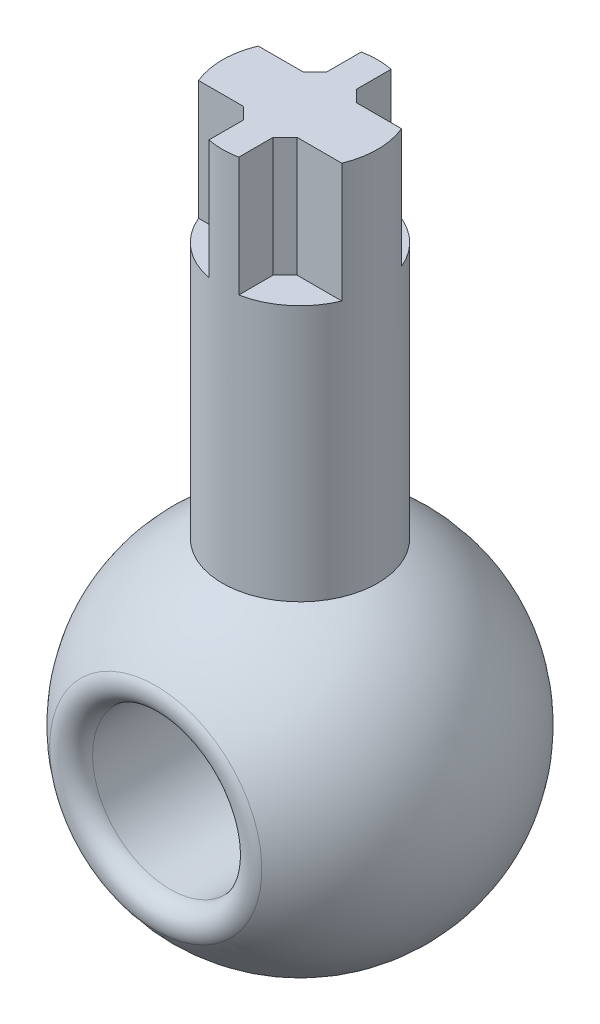
SolidWorks part; units mm, degrees
ref_plane "Plane1" through (0, 0, 0) normal (0, 0, 1) x (1, 0, 0)
ref_plane "Plane2" through (0, 0, 0) normal (0, 1, 0) x (1, 0, 0)
ref_plane "Plane3" through (0, 0, 0) normal (1, 0, 0) x (0, 0, -1)
sketch "s1" plane through (0, 0, 0) normal (0, 0, 1) x (1, 0, 0)
  line L0 (-56.6721, 0) -> (83.8972, 0) construction
  line L1 (-15, 0) -> (15, 0)
  arc A0 (15, 0) -> (-15, 0) centre (0, 0) ccw
  dimension "D1" = 15
revolve "1" add sketch "s1" angle 360 about L0
sketch "s2" plane through (0, 0, 0) normal (0, 1, 0) x (1, 0, 0)
  circle A0 centre (0, 0) radius 6.5
  dimension "D1" = 13
extrude "2" add sketch "s2" along normal blind 45
sketch "s3" plane through (0, 45, 0) normal (0, 1, 0) x (-1, 0, 0)
  line L0 (-10.6288, 0) -> (13.9677, 0) construction
  line L1 (56.6721, 0) -> (-83.8972, 0) construction
  line L2 (0, -10.8514) -> (0, 14.1903) construction
  line L3 (-1.25, -6.3787) -> (-1.25, -2.5)
  line L4 (1.25, -6.3787) -> (1.25, -2.5)
  line L5 (-6, 2.5) -> (-1.25, 2.5)
  line L6 (-6, -2.5) -> (-1.25, -2.5)
  line L7 (-1.25, 2.5) -> (-1.25, 6.3787)
  line L8 (1.25, 2.5) -> (1.25, 6.3787)
  line L9 (1.25, -2.5) -> (6, -2.5)
  line L10 (1.25, 2.5) -> (6, 2.5)
  circle A0 centre (0, 0) radius 6.5 construction
  arc A1 (-6, -2.5) -> (-1.25, -6.3787) centre (0, 0) ccw
  arc A2 (6, 2.5) -> (1.25, 6.3787) centre (0, 0) ccw
  arc A3 (-1.25, 6.3787) -> (-6, 2.5) centre (0, 0) ccw
  arc A4 (1.25, -6.3787) -> (6, -2.5) centre (0, 0) ccw
  dimension "D1" = 5
  dimension "D2" = 2.5
extrude "3" cut sketch "s3" against normal blind 10
chamfer "4" distance 1 angle 45 4 edges at (-1.25, 40, -2.5) (1.25, 40, -2.5) (1.25, 40, 2.5) (-1.25, 40, 2.5)
sketch "s5" plane through (0, 0, 0) normal (0, 0, 1) x (1, 0, 0)
  circle A0 centre (0, 0) radius 6.5
  dimension "D1" = 13
extrude "5" cut sketch "s5" against normal through all and the other way through all
fillet "Fillet1" radius 1.5 2 edges at (6.5, 0, -13.5185) (-6.5, 0, 13.5185)
